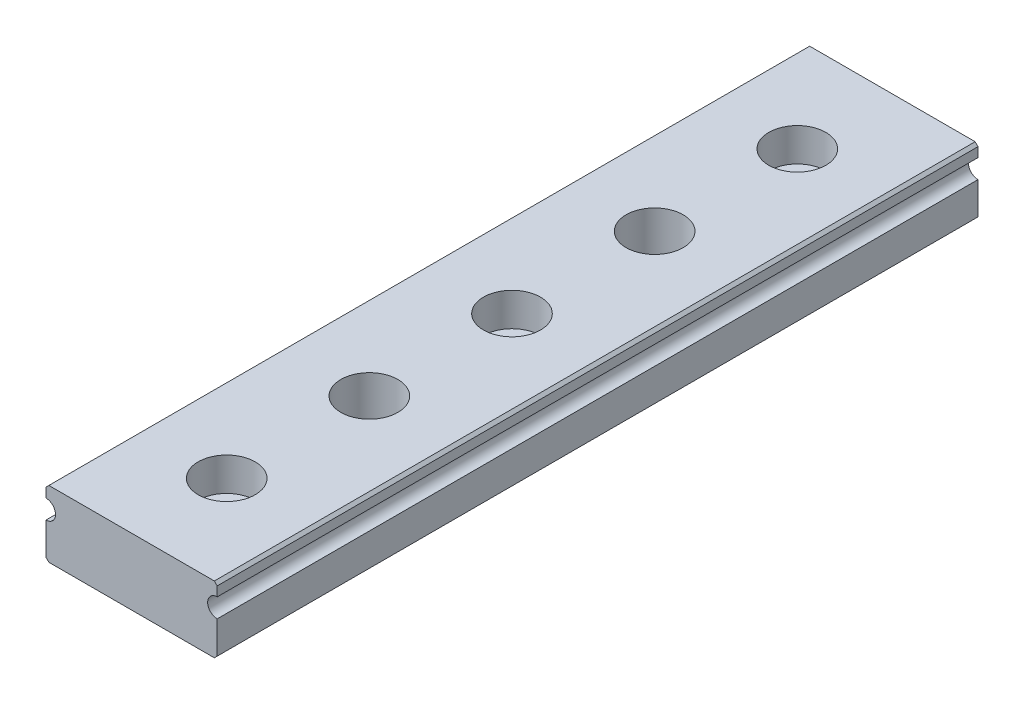
SolidWorks part; units mm, degrees
material "AISI 1020"
ref_plane "Front Plane" through (0, 0, 0) normal (0, 0, 1) x (1, 0, 0)
ref_plane "Top Plane" through (0, 0, 0) normal (0, 1, 0) x (1, 0, 0)
ref_plane "Right Plane" through (0, 0, 0) normal (1, 0, 0) x (0, 0, -1)
ref_plane "Plano1" through (0, 0, 0) normal (0, -1, 0) x (1, 0, 0)
sketch "Esboço1" plane through (0, 0, 0) normal (0, -1, 0) x (1, 0, 0)
  line L0 (-18, -80) -> (0, -80)
  line L1 (0, -80) -> (0, 0)
  line L2 (0, 0) -> (-18, 0)
  line L3 (-18, 0) -> (-18, -80)
  dimension "D1" = 80
  dimension "D2" = 18
extrude "Ressalto-extrusão1" add sketch "Esboço1" against normal blind 7
hole_wizard "Furo de diâmetro Ø2.0 (2)1" positions "Esboço5" profile "Esboço4" hole size "Ø2.0" standard "Ansi Metric" end condition through all
sketch "Esboço5" plane through (0, 0, -80) normal (0, 0, -1) x (-1, 0, 0)
  line L0 (0, 0) -> (18, 0) construction
  line L1 (18, 7) -> (18, 0) construction
  point P0 (0, 4.7)
  point P1 (18, 4.7)
  dimension "D1" = 18
  dimension "D2" = 4.7
sketch "Esboço4" plane through (0, 4.7, -80) normal (1, 0, 0) x (0, 1, 0)
  line L0 (0, 0) -> (0, 80)
  line L1 (0, 80) -> (1, 80)
  line L2 (1, 80) -> (1, 0)
  line L5 (1, 0) -> (0, 0)
  line L11 (0, -6.35) -> (0, 107.95) construction
  dimension "Thru Hole Dia." = 2
  dimension "Thru Hole Depth" = 80
hole_wizard "Furo de diâmetro Ø6.0 (6)1" positions "Esboço3" profile "Esboço2" hole size "Ø6.0" standard "Ansi Metric" end condition through all
sketch "Esboço3" plane through (0, 7, 0) normal (0, 1, 0) x (1, 0, 0)
  line L0 (0, 80) -> (0, 0) construction
  line L1 (0, 0) -> (-18, 0) construction
  point P0 (-9, 25)
  dimension "D3" = 9
  dimension "D4" = 25
sketch "Esboço2" plane through (-9, 7, -25) normal (1, 0, 0) x (0, 0, 1)
  line L0 (0, 0) -> (0, 7)
  line L1 (0, 7) -> (3, 7)
  line L2 (3, 7) -> (3, 0)
  line L5 (3, 0) -> (0, 0)
  line L11 (0, -6.35) -> (0, 107.95) construction
  dimension "Thru Hole Dia." = 6
  dimension "Thru Hole Depth" = 7
hole_wizard "Rebaixo para parafuso de máquina de cabeça sextavada de M31" positions "Esboço9" profile "Esboço8" counterbore size "M3" standard "Ansi Metric" end condition through all
sketch "Esboço9" plane through (0, 7, 0) normal (0, 1, 0) x (1, 0, 0)
  line L0 (0, 80) -> (0, 0) construction
  line L3 (0, 0) -> (-18, 0) construction
  point P2 (-9, 10)
  dimension "D3" = 9
  dimension "D6" = 10
sketch "Esboço8" plane through (-9, 7, -10) normal (1, 0, 0) x (0, 0, 1)
  line L0 (0, 0) -> (0, 7)
  line L1 (0, 7) -> (1.75, 7)
  line L3 (1.75, 7) -> (1.75, 3.5)
  line L4 (1.75, 3.5) -> (3, 3.5)
  line L5 (3, 3.5) -> (3, 0)
  line L7 (3, 0) -> (0, 0)
  line L11 (0, -6.35) -> (0, 107.95) construction
  dimension "Thru Hole Dia." = 3.5
  dimension "Thru Hole Depth" = 7
  dimension "C'Bore Dia." = 6
  dimension "C'Bore Depth" = 3.5
pattern_linear "Padrão linear1" count 2 spacing 30 along (0, 0, -1) of "Furo de diâmetro Ø6.0 (6)1"
pattern_linear "Padrão linear2" count 3 spacing 30 along (0, 0, -1) of "Rebaixo para parafuso de máquina de cabeça sextavada de M31"
chamfer "Chanfro1" distance 0.3 angle 45 4 edges at (-18, 7, -40) (0, 7, -40) (0, 0, -40) (-18, 0, -40)
